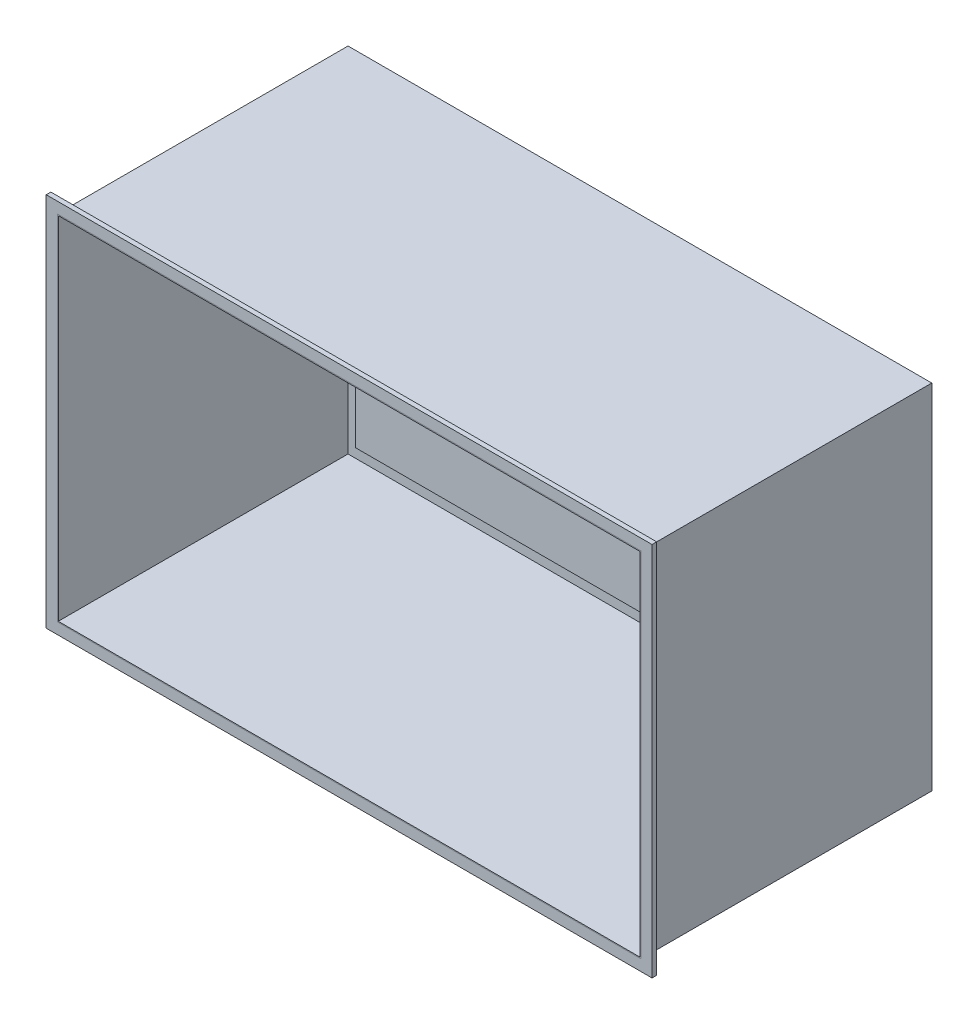
SolidWorks part; units mm, degrees
ref_plane "Alzado" through (0, 0, 0) normal (0, 0, 1) x (1, 0, 0)
ref_plane "Planta" through (0, 0, 0) normal (0, 1, 0) x (1, 0, 0)
ref_plane "Vista lateral" through (0, 0, 0) normal (1, 0, 0) x (0, 0, -1)
sketch "Croquis1" plane through (0, 0, 0) normal (0, 1, 0) x (1, 0, 0)
  line L1 (-396.5, 220) -> (396.5, 220)
  line L2 (-396.5, 220) -> (-396.5, -220)
  line L3 (-396.5, -220) -> (396.5, -220)
  line L4 (396.5, 220) -> (396.5, -220)
  line L5 (-396.5, 220) -> (396.5, -220) construction
  line L6 (-396.5, -220) -> (396.5, 220) construction
  point P0 (0, 0)
  dimension "D1" = 793
  dimension "D2" = 440
extrude "Saliente-Extruir1" add sketch "Croquis1" along normal blind 480
shell "Vaciado1" thickness 1.36
sketch "Croquis2" plane through (0, 0, 0) normal (0, -1, 0) x (1, 0, 0)
  line L0 (-327.9814, 41.2887) -> (-340.6814, 41.2887) construction
  line L1 (-346.5, 30) -> (-346.5, -220) construction
  line L2 (396.5, -220) -> (-396.5, -220) construction
  line L3 (-396.5, -220) -> (-396.5, 220) construction
  circle A0 centre (-340.6814, 41.2887) radius 12.7
  dimension "D1" = 25.4
  dimension "D2" = 250
  dimension "D3" = 50
extrude "Cortar-Extruir1" cut sketch "Croquis2" against normal blind 80
sketch "Croquis3" plane through (0, 0, 0) normal (0, -1, 0) x (1, 0, 0)
  line L0 (-340.6814, 41.2887) -> (-340.6814, 81.2887) construction
  circle A0 centre (-340.6814, 81.2887) radius 6.35
  dimension "D1" = 12.7
  dimension "D2" = 40
extrude "Cortar-Extruir2" cut sketch "Croquis3" against normal blind 10
sketch "Croquis5" plane through (0, 0, 0) normal (0, -1, 0) x (1, 0, 0)
  line L0 (-340.6814, 81.2887) -> (-340.6814, 121.2887) construction
  circle A0 centre (-340.6814, 121.2887) radius 6.35
  dimension "D2" = 12.7
  dimension "D1" = 40
extrude "Cortar-Extruir4" cut sketch "Croquis5" against normal blind 10
sketch "Croquis6" plane through (-396.5, 0, 0) normal (-1, 0, 0) x (0, 0, 1)
  line L0 (70, 450) -> (220, 450) construction
  line L1 (220, 480) -> (220, 0) construction
  line L2 (70, 450) -> (70, 480) construction
  line L3 (-220, 480) -> (220, 480) construction
  line L4 (70, 450) -> (-219.4947, 450) construction
  circle A0 centre (-130, 450) radius 19.05
  circle A1 centre (70, 450) radius 19.05
  dimension "D4" = 38.1
  dimension "D5" = 38.1
  dimension "D1" = 150
  dimension "D2" = 30
  dimension "D3" = 200
sketch "Croquis7" plane through (0, 0, 0) normal (0, -1, 0) x (1, 0, 0)
  line L0 (0, 0) -> (0, 220) construction
  line L1 (-396.5, 220) -> (396.5, 220) construction
mirror "Simetría1" about plane through (0, 0, 0) normal (1, 0, 0) of "Cortar-Extruir1", "Cortar-Extruir2", "Cortar-Extruir4"
sketch "Croquis8" plane through (0, 0, 0) normal (0, -1, 0) x (1, 0, 0)
  line L0 (340.6814, 28.5887) -> (340.6814, -121.4113) construction
  circle A0 centre (340.6814, 41.2887) radius 12.7 construction
  circle A1 centre (340.6814, -121.4113) radius 12.7
  dimension "D1" = 25.4
  dimension "D2" = 150
extrude "Cortar-Extruir6" cut sketch "Croquis8" against normal blind 10
sketch "Croquis9" plane through (0, 1.36, 0) normal (0, 1, 0) x (1, 0, 0)
  line L1 (-353.5542, -6.5775) -> (-327.8087, -6.5775)
  line L2 (-353.5542, -6.5775) -> (-353.5542, -155.9999)
  line L3 (-353.5542, -155.9999) -> (-327.8087, -155.9999)
  line L4 (-327.8087, -6.5775) -> (-327.8087, -155.9999)
  line L5 (-353.5542, -6.5775) -> (-327.8087, -155.9999) construction
  line L6 (-353.5542, -155.9999) -> (-327.8087, -6.5775) construction
  point P0 (-340.6814, -81.2887)
  point P6 (-327.8087, -155.9999)
extrude "Saliente-Extruir2" add sketch "Croquis9" against normal blind 1.36
sketch "Croquis10" plane through (0, 0, 0) normal (0, -1, 0) x (-1, 0, 0)
  line L0 (275, 175) -> (396.5, 175) construction
  line L1 (396.5, 220) -> (396.5, -220) construction
  line L2 (275, 175) -> (275, 220) construction
  line L3 (-396.5, 220) -> (396.5, 220) construction
  circle A0 centre (-275, 175) radius 3.97
  circle A1 centre (-275, -81.2) radius 3.97
  circle A2 centre (275, 175) radius 3.9688
  circle A3 centre (275, -81.2) radius 3.97
  dimension "D1" = 7.94
  dimension "D2" = 7.94
  dimension "D3" = 7.94
sketch "Croquis12" plane through (0, 0, -218.64) normal (0, 0, 1) x (1, 0, 0)
  line L0 (0, 1.36) -> (0, 478.64) construction
  line L1 (-395.14, 1.36) -> (395.14, 1.36) construction
  line L2 (395.14, 478.64) -> (-395.14, 478.64) construction
  line L3 (0, 240) -> (24.0252, 240) construction
  line L4 (-395.14, 478.64) -> (395.14, 478.64) construction
  line L5 (-375.14, 21.36) -> (375.14, 21.36)
  line L6 (-375.14, 21.36) -> (-375.14, 458.64)
  line L7 (-375.14, 458.64) -> (375.14, 458.64)
  line L8 (375.14, 21.36) -> (375.14, 458.64)
  line L9 (-375.14, 21.36) -> (375.14, 458.64) construction
  line L10 (-375.14, 458.64) -> (375.14, 21.36) construction
  line L11 (395.14, 478.64) -> (395.14, 1.36) construction
  dimension "D1" = 20
  dimension "D2" = 20
sketch "Croquis13" plane through (395.14, 0, 0) normal (-1, 0, 0) x (0, 0, 1)
  line L0 (0.68, 1.36) -> (0.68, 478.64) construction
  line L1 (220, 1.36) -> (-218.64, 1.36) construction
  line L2 (220, 478.64) -> (-218.64, 478.64) construction
  line L3 (0.68, 478.64) -> (0.68, 240) construction
  line L4 (0.68, 240) -> (45.2661, 240) construction
  line L5 (220, 478.64) -> (220, 1.36) construction
  line L6 (-198.64, 458.64) -> (200, 458.64)
  line L7 (-198.64, 458.64) -> (-198.64, 21.36)
  line L8 (-198.64, 21.36) -> (200, 21.36)
  line L9 (200, 458.64) -> (200, 21.36)
  line L10 (-198.64, 458.64) -> (200, 21.36) construction
  line L11 (-198.64, 21.36) -> (200, 458.64) construction
  dimension "D1" = 20
  dimension "D2" = 20
sketch "Croquis14" plane through (-396.5, 0, 0) normal (-1, 0, 0) x (0, 0, 1)
  line L0 (-188.64, 480) -> (-188.64, 398.64) construction
  line L1 (-198.64, 21.36) -> (200, 21.36)
  line L2 (-198.64, 21.36) -> (-198.64, 458.64)
  line L3 (-198.64, 458.64) -> (200, 458.64)
  line L4 (200, 21.36) -> (200, 458.64)
  line L5 (-198.64, 21.36) -> (200, 458.64) construction
  line L6 (-198.64, 458.64) -> (200, 21.36) construction
  line L7 (-220, 480) -> (220, 480) construction
  line L8 (-188.64, 398.64) -> (-220, 398.64) construction
  line L9 (-220, 480) -> (-220, 0) construction
  line L10 (-198.64, 458.64) -> (-198.64, 408.64)
  line L11 (-198.64, 408.64) -> (200, 408.64)
  line L12 (0.68, 240) -> (45.2661, 240) construction
  line L13 (0.68, 240) -> (0.68, 173.2105) construction
  line L14 (0.68, 1.36) -> (0.68, 478.64) construction
  circle A0 centre (-188.64, 398.64) radius 3.175
  circle A1 centre (190, 398.64) radius 3.175
  circle A2 centre (-188.64, 31.36) radius 3.175 construction
  circle A3 centre (190, 31.36) radius 3.175 construction
  circle A4 centre (-198.64, 21.36) radius 3.175
  circle A5 centre (200, 21.36) radius 3.175
  point P0 (0.68, 240)
  dimension "D4" = 6.35
  dimension "D5" = 10
  dimension "D6" = 10
  dimension "D7" = 6.35
  dimension "D8" = 6.35
  dimension "D9" = 6.35
  dimension "D1" = 10
  dimension "D2" = 10
  dimension "D3" = 50
sketch "Croquis15" plane through (0, 0, 0) normal (0, -1, 0) x (1, 0, 0)
  line L0 (-366.5, -120) -> (-366.5, -220) construction
  line L1 (-366.5, -120) -> (-396.5, -120) construction
  line L2 (-396.5, -220) -> (-396.5, 220) construction
  line L3 (0, 0) -> (0, -220) construction
  line L4 (396.5, -220) -> (-396.5, -220) construction
  line L5 (0, 0) -> (14.2284, 0) construction
  line L6 (0, -15) -> (113.2183, -15) construction
  line L7 (-366.5, 220) -> (-366.5, 90) construction
  line L8 (-396.5, 220) -> (396.5, 220) construction
  circle A0 centre (-366.5, -120) radius 3.175
  circle A1 centre (-366.5, 90) radius 3.175
  circle A2 centre (366.5, -120) radius 3.175
  circle A3 centre (366.5, 90) radius 3.175
  dimension "D3" = 6.35
  dimension "D1" = 30
  dimension "D2" = 100
  dimension "D4" = 130
sketch "Croquis16" plane through (-396.5, 0, 0) normal (-1, 0, 0) x (0, 0, 1)
  line L0 (220, 480) -> (220, 0) construction
  line L1 (-225, 401.7269) -> (220, 401.7269)
  line L2 (-225, 401.7269) -> (-225, 0)
  line L3 (-225, 0) -> (220, 0)
  line L4 (220, 401.7269) -> (220, 0)
  line L5 (-225, 401.7269) -> (220, 0) construction
  line L6 (-225, 0) -> (220, 401.7269) construction
  point P0 (-2.5, 200.8635)
sketch "Croquis18" plane through (0, 0, -218.64) normal (0, 0, 1) x (1, 0, 0)
  line L0 (-348.7422, 441.087) -> (-348, 438) construction
  line L1 (-348, 438) -> (-344.913, 438.7422) construction
  circle A0 centre (-348, 438) radius 3.175
  circle A1 centre (0, 438) radius 3.175
  circle A2 centre (348, 438) radius 3.175
  circle A3 centre (348, 240) radius 3.175
  circle A4 centre (348, 42) radius 3.175
  circle A5 centre (0, 42) radius 3.175
  circle A6 centre (-348, 42) radius 3.175
  circle A7 centre (-348, 240) radius 5.5549
extrude "Cortar-Extruir12" cut sketch "Croquis18" against normal blind 10
sketch "Croquis19" plane through (0, 0, 220) normal (0, 0, 1) x (1, 0, 0)
  line L0 (-395.14, 240) -> (0, 240) construction
  line L1 (-395.14, 478.64) -> (-395.14, 1.36) construction
  line L2 (0, 240) -> (0, 0) construction
  line L4 (-396.5, 0) -> (396.5, 0)
  line L5 (-396.5, 0) -> (-396.5, 480)
  line L6 (-396.5, 480) -> (396.5, 480)
  line L7 (396.5, 0) -> (396.5, 480)
  line L8 (-396.5, 0) -> (396.5, 480) construction
  line L9 (-396.5, 480) -> (396.5, 0) construction
extrude "Cortar-Extruir13" cut sketch "Croquis19" against normal blind 45
sketch "Croquis20" plane through (0, 0, 0) normal (0, -1, 0) x (1, 0, 0)
  line L1 (316.4197, 137.6096) -> (356.6426, 137.6096)
  line L2 (316.4197, 137.6096) -> (316.4197, -197.5808)
  line L3 (316.4197, -197.5808) -> (356.6426, -197.5808)
  line L4 (356.6426, 137.6096) -> (356.6426, -197.5808)
  line L5 (316.4197, 137.6096) -> (356.6426, -197.5808) construction
  line L6 (316.4197, -197.5808) -> (356.6426, 137.6096) construction
  point P0 (336.5311, -29.9856)
extrude "Saliente-Extruir3" add sketch "Croquis20" against normal blind 1.36
sketch "Croquis21" plane through (0, 0, 0) normal (0, -1, 0) x (1, 0, 0)
  line L0 (396.5, -220) -> (316.5, -220) construction
  line L1 (396.5, -220) -> (-396.5, -220) construction
  line L2 (316.5, -220) -> (316.5, 175) construction
  line L3 (-396.5, 175) -> (396.5, 175) construction
  circle A0 centre (316.5, -144.9784) radius 12.7
  dimension "D2" = 25.4
  dimension "D1" = 80
sketch "Croquis22" plane through (0, 0, -220) normal (0, 0, -1) x (-1, 0, 0)
  line L1 (-375.2804, 466.7691) -> (379.4355, 466.7691)
  line L2 (-375.2804, 466.7691) -> (-375.2804, 19.4447)
  line L3 (-375.2804, 19.4447) -> (379.4355, 19.4447)
  line L4 (379.4355, 466.7691) -> (379.4355, 19.4447)
  line L5 (-375.2804, 466.7691) -> (379.4355, 19.4447) construction
  line L6 (-375.2804, 19.4447) -> (379.4355, 466.7691) construction
  point P0 (2.0775, 243.1069)
extrude "Saliente-Extruir4" add sketch "Croquis22" against normal blind 7
sketch "Croquis23" plane through (0, 0, 175) normal (0, 0, 1) x (1, 0, 0)
  line L0 (-396.5, 480) -> (396.5, 480)
  line L1 (396.5, 480) -> (396.5, 0)
  line L2 (396.5, 0) -> (-396.5, 0)
  line L3 (-396.5, 0) -> (-396.5, 480)
  line L4 (-411.5, -15) -> (-411.5, 495)
  line L5 (-411.5, 495) -> (411.5, 495)
  line L6 (411.5, 495) -> (411.5, -15)
  line L7 (411.5, -15) -> (-411.5, -15)
  dimension "D1" = 15
extrude "Saliente-Extruir5" add sketch "Croquis23" against normal blind 6.31 separate body
sketch "Croquis24" plane through (0, 0, 0) normal (0, -1, 0) x (1, 0, 0)
  line L2 (372.5, -117.8) -> (396.5, -117.8) construction
  line L3 (396.5, 175) -> (396.5, -220) construction
  line L4 (372.5, -105.1) -> (372.5, -80.1) construction
  line L5 (372.5, -54.7) -> (372.5, -29.7) construction
  line L6 (372.5, -130.5) -> (385.2, -130.5) construction
  line L7 (396.5, -220) -> (-396.5, -220) construction
  circle A0 centre (372.5, -117.8) radius 12.7
  circle A1 centre (372.5, -67.4) radius 12.7
  circle A2 centre (372.5, -17) radius 12.7
  dimension "D2" = 25.4
  dimension "D6" = 25.4
  dimension "D7" = 25.4
  dimension "D1" = 24
  dimension "D3" = 89.5
  dimension "D4" = 25
  dimension "D5" = 25
extrude "Cortar-Extruir14" cut sketch "Croquis24" against normal blind 10
